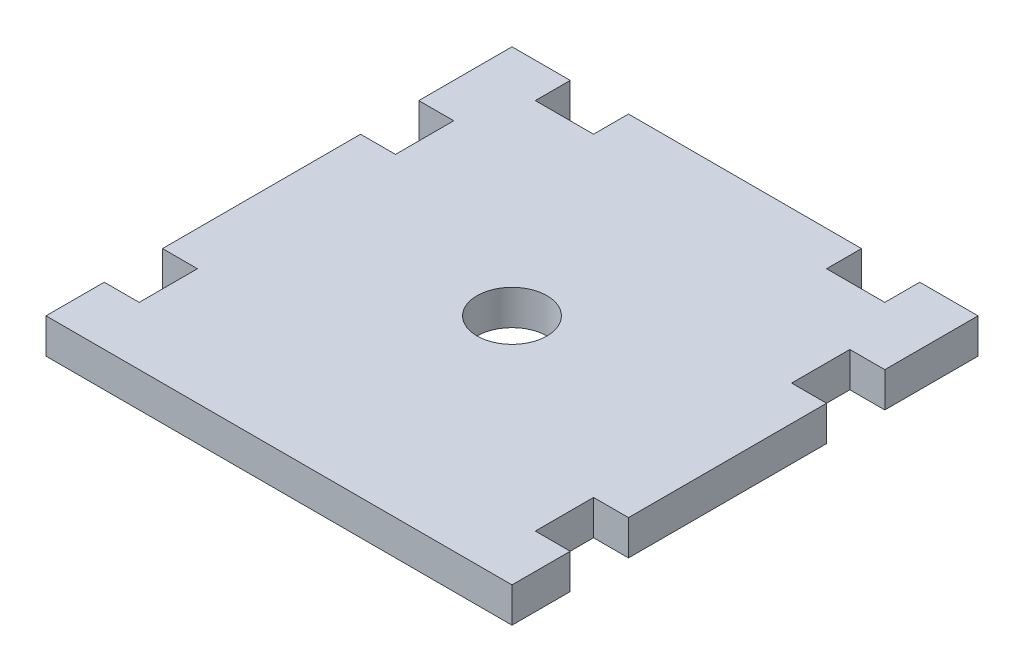
SolidWorks part; units mm, degrees
ref_plane "Front Plane" through (0, 0, 0) normal (0, 0, 1) x (1, 0, 0)
ref_plane "Top Plane" through (0, 0, 0) normal (0, 1, 0) x (1, 0, 0)
ref_plane "Right Plane" through (0, 0, 0) normal (1, 0, 0) x (0, 0, -1)
sketch "Sketch1" plane through (0, 0, 0) normal (0, 1, 0) x (1, 0, 0)
  line L1 (-20, -20) -> (20, -20)
  line L2 (-20, -20) -> (-20, 20)
  line L3 (-20, 20) -> (20, 20)
  line L4 (20, -20) -> (20, 20)
  line L5 (0, 20) -> (0, -20) construction
  line L6 (-20, 0) -> (20, 0) construction
  point P0 (0, 0)
  dimension "D1" = 40
  dimension "D2" = 40
extrude "Boss-Extrude1" add sketch "Sketch1" along normal blind 3
sketch "Sketch2" plane through (0, 3, 0) normal (0, 1, 0) x (1, 0, 0)
  circle A0 centre (0, 0) radius 3
extrude "Cut-Extrude1" cut sketch "Sketch2" against normal blind 3
sketch "Sketch3" plane through (0, 0, 0) normal (0, -1, 0) x (1, 0, 0)
  line L0 (20, -17) -> (-20, -17) construction
  line L1 (20, 20) -> (20, -20) construction
  line L2 (-20, -20) -> (-20, 20) construction
  line L3 (20, -20) -> (-20, -20) construction
  line L4 (0, -17) -> (0, -20) construction
  line L5 (15, -20) -> (10, -20)
  line L6 (15, -20) -> (15, -17)
  line L7 (15, -17) -> (10, -17)
  line L8 (10, -20) -> (10, -17)
  line L9 (-15, -17) -> (-10, -17)
  line L10 (-10, -20) -> (-10, -17)
  line L11 (-15, -20) -> (-10, -20)
  line L12 (-15, -20) -> (-15, -17)
  dimension "D1" = 3
  dimension "D2" = 5
  dimension "D3" = 5
extrude "Cut-Extrude2" cut sketch "Sketch3" against normal blind 10
sketch "Sketch4" plane through (0, 0, 0) normal (0, -1, 0) x (1, 0, 0)
  line L0 (20, 20) -> (20, -20) construction
  line L1 (17, 15) -> (20, 15)
  line L2 (17, 15) -> (17, 10)
  line L3 (17, 10) -> (20, 10)
  line L4 (20, 15) -> (20, 10)
  line L5 (17, 10) -> (20, 10) construction
  line L6 (17, -12) -> (20, -12) construction
  line L7 (17, -7) -> (20, -7)
  line L8 (17, -7) -> (17, -12)
  line L9 (17, -12) -> (20, -12)
  line L10 (20, -7) -> (20, -12)
  line L11 (0, 0) -> (0, -20) construction
  line L12 (-17, -12) -> (-20, -12)
  line L13 (-20, -7) -> (-20, -12)
  line L14 (-17, -7) -> (-20, -7)
  line L15 (-17, -7) -> (-17, -12)
  line L16 (-17, 10) -> (-20, 10)
  line L17 (-20, 15) -> (-20, 10)
  line L18 (-17, 15) -> (-20, 15)
  line L19 (-17, 15) -> (-17, 10)
extrude "Cut-Extrude3" cut sketch "Sketch4" against normal blind 3
